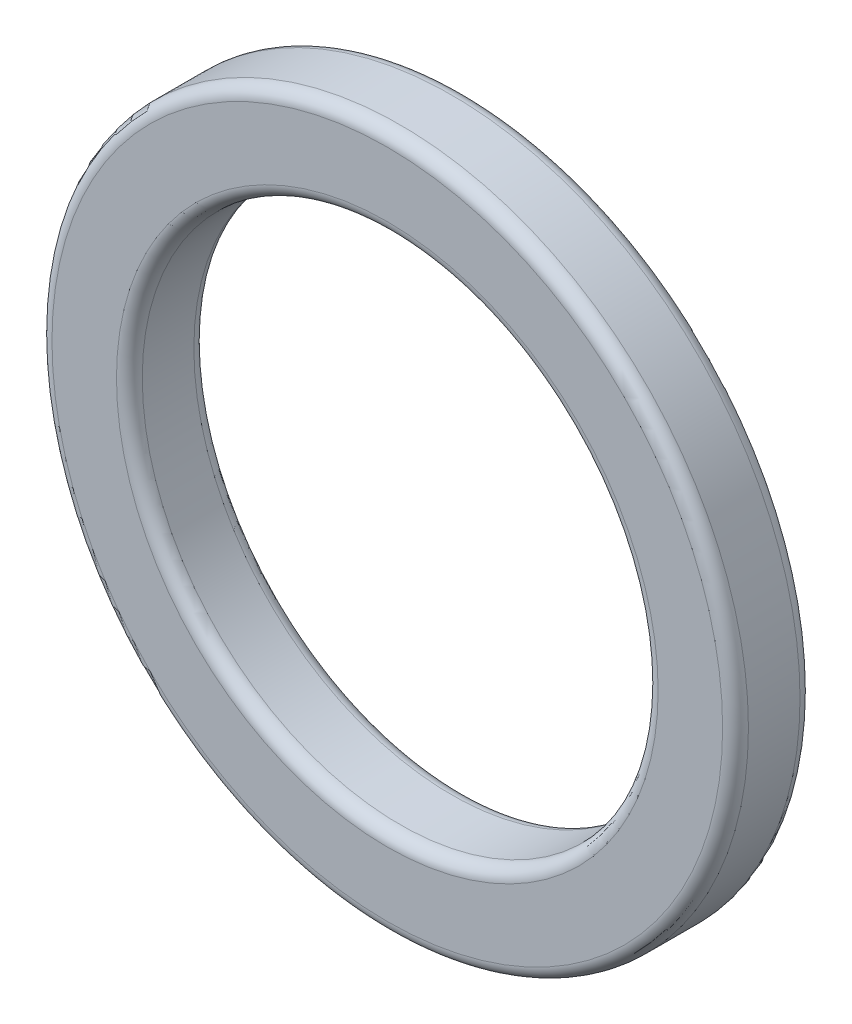
SolidWorks part; units mm, degrees
material "ABS PC"
ref_plane "Front Plane" through (0, 0, 0) normal (0, 0, 1) x (1, 0, 0)
ref_plane "Top Plane" through (0, 0, 0) normal (0, 1, 0) x (1, 0, 0)
ref_plane "Right Plane" through (0, 0, 0) normal (1, 0, 0) x (0, 0, -1)
sketch "Sketch1" plane through (0, 0, 0) normal (0, 0, 1) x (1, 0, 0)
  circle A0 centre (0, 0) radius 0.675
  circle A1 centre (0, 0) radius 0.5
  dimension "D1" = 1.35
  dimension "D2" = 1
extrude "Boss-Extrude1" add sketch "Sketch1" along normal blind 0.15
fillet "Fillet1" radius 0.025 4 edges at (0.5, 0, 0) (0.675, 0, 0) (0.5, 0, 0.15) (0.675, 0, 0.15)
